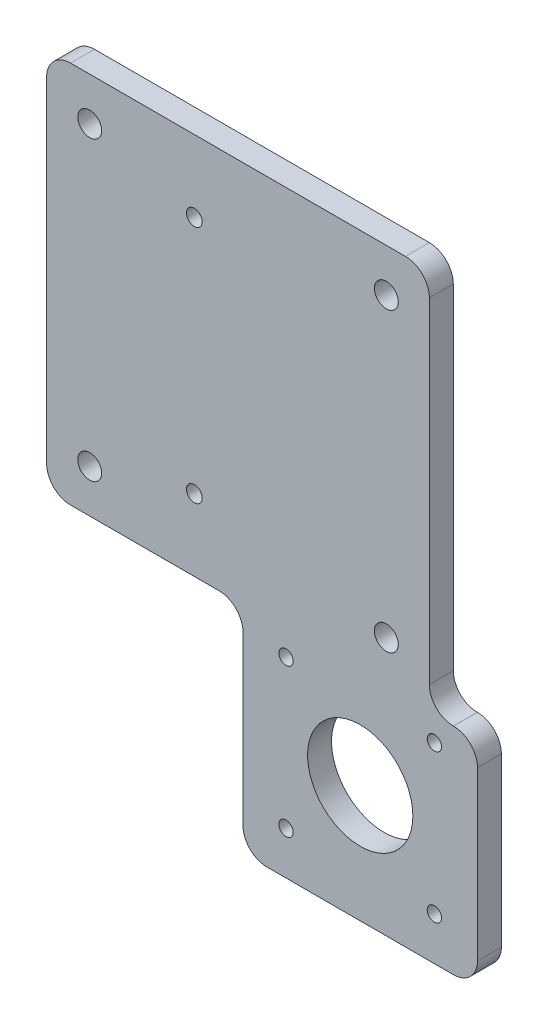
SolidWorks part; units mm, degrees
ref_plane "Front Plane" through (0, 0, 0) normal (0, 0, 1) x (1, 0, 0)
ref_plane "Top Plane" through (0, 0, 0) normal (0, 1, 0) x (1, 0, 0)
ref_plane "Right Plane" through (0, 0, 0) normal (1, 0, 0) x (0, 0, -1)
sketch "Sketch1" plane through (0, 0, 0) normal (0, 0, 1) x (1, 0, 0)
  line L0 (20.8688, 91.6472) -> (20.8688, -9.2883) construction
  line L2 (0, 0) -> (0, 80)
  line L3 (0, 80) -> (80, 80)
  line L4 (80, 0) -> (80, 80)
  line L5 (40.8688, 91.6472) -> (40.8688, -9.2883) construction
  line L6 (-23.2123, 60) -> (94.163, 60) construction
  line L7 (-23.2123, 20) -> (94.163, 20) construction
  line L8 (0, 0) -> (41.0437, 0)
  line L9 (41.0437, 0) -> (41.0437, -45)
  line L10 (41.0437, -45) -> (90.0437, -45)
  line L11 (90.0437, -45) -> (90.0437, 0)
  line L12 (90.0437, 0) -> (80, 0)
  line L13 (18.9321, -5) -> (80.2845, -5) construction
  line L14 (18.9321, -36) -> (80.2845, -36) construction
  line L15 (50.0437, -5) -> (50.0437, -36) construction
  line L16 (81.0437, -5) -> (81.0437, -36) construction
  line L17 (50.0437, -5) -> (81.0437, -36) construction
  line L18 (81.0437, -5) -> (50.0437, -36) construction
  circle A0 centre (9, 71) radius 12 construction
  circle A1 centre (9, 71) radius 2.5
  circle A2 centre (71, 71) radius 2.5
  circle A3 centre (71, 9) radius 2.5
  circle A4 centre (9, 9) radius 2.5
  circle A5 centre (50.0437, -5) radius 1.5
  circle A6 centre (81.0437, -5) radius 1.5
  circle A7 centre (71, 9) radius 12 construction
  circle A8 centre (50.0437, -36) radius 1.5
  circle A9 centre (81.0437, -36) radius 1.5
  circle A10 centre (65.5437, -20.5) radius 11
  circle A11 centre (30.8688, 15) radius 1.65
  circle A12 centre (30.8688, 65) radius 1.65
  point P45 (30.8688, 65.0129)
  dimension "D5" = 20
  dimension "D6" = 11
  dimension "D9" = 2
  dimension "D11" = 31
  dimension "D13" = 9
  dimension "D16" = 10
  dimension "D17" = 50
  dimension "D19" = 5
  dimension "D1" = 80
  dimension "D2" = 80
  dimension "D3" = 20
  dimension "D4" = 40
  dimension "D7" = 9
  dimension "D8" = 9
  dimension "D12" = 31
  dimension "D14" = 9
  dimension "D15" = 9
  dimension "D18" = 15
  dimension "D10" = 2
extrude "Boss-Extrude1" add sketch "Sketch1" along normal blind 5
fillet "Fillet1" radius 5 8 edges at (80, 0, 2.5) (90.0437, 0, 2.5) (0, 80, 2.5) (80, 80, 2.5) (90.0437, -45, 2.5) (0, 0, 2.5) (41.0437, -45, 2.5) (41.0437, 0, 2.5)
